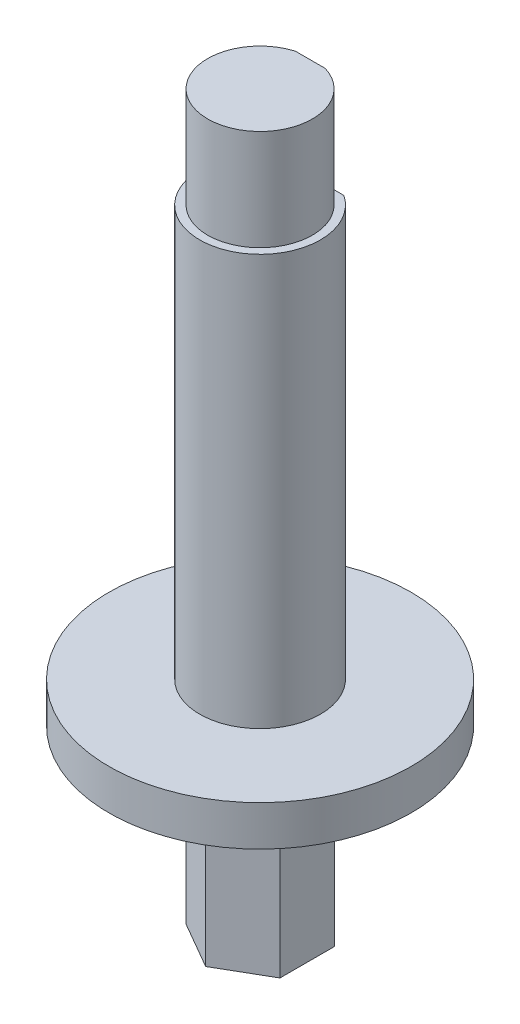
SolidWorks part; units mm, degrees
ref_plane "Front" through (0, 0, 0) normal (0, 0, 1) x (1, 0, 0)
ref_plane "Top" through (0, 0, 0) normal (0, 1, 0) x (1, 0, 0)
ref_plane "Right" through (0, 0, 0) normal (1, 0, 0) x (0, 0, -1)
sketch "Sketch1" plane through (0, 0, 0) normal (0, 1, 0) x (1, 0, 0)
  line L1 (0, 2.7) -> (-2.3383, 1.35)
  line L2 (-2.3383, 1.35) -> (-2.3383, -1.35)
  line L3 (-2.3383, -1.35) -> (0, -2.7)
  line L4 (0, -2.7) -> (2.3383, -1.35)
  line L5 (2.3383, -1.35) -> (2.3383, 1.35)
  line L6 (2.3383, 1.35) -> (0, 2.7)
  circle A0 centre (0, 0) radius 2.3383 construction
  dimension "D1" = 2.7
extrude "Boss-Extrude1" add sketch "Sketch1" along normal blind 9
sketch "Sketch2" plane through (0, 9, 0) normal (0, 1, 0) x (1, 0, 0)
  line L0 (-1.6678, 2.4937) -> (1.6678, 2.4937)
  arc A0 (-1.6678, 2.4937) -> (1.6678, 2.4937) centre (0, 0) ccw
  point P6 (0, 2.4937)
extrude "Boss-Extrude2" add sketch "Sketch2" along normal blind 22.4
sketch "Sketch3" plane through (0, 9, 0) normal (0, -1, 0) x (1, 0, 0)
  circle A0 centre (0, 0) radius 7.5
extrude "Boss-Extrude3" add sketch "Sketch3" against normal blind 2
sketch "Sketch4" plane through (0, 31.4, 0) normal (0, 1, 0) x (1, 0, 0)
  line L1 (1.6678, 2.4937) -> (-1.6678, 2.4937) construction
  line L2 (-0.736, 2.4937) -> (0.736, 2.4937)
  arc A0 (-0.736, 2.4937) -> (0.736, 2.4937) centre (0, 0) ccw
extrude "Boss-Extrude4" add sketch "Sketch4" along normal blind 5
